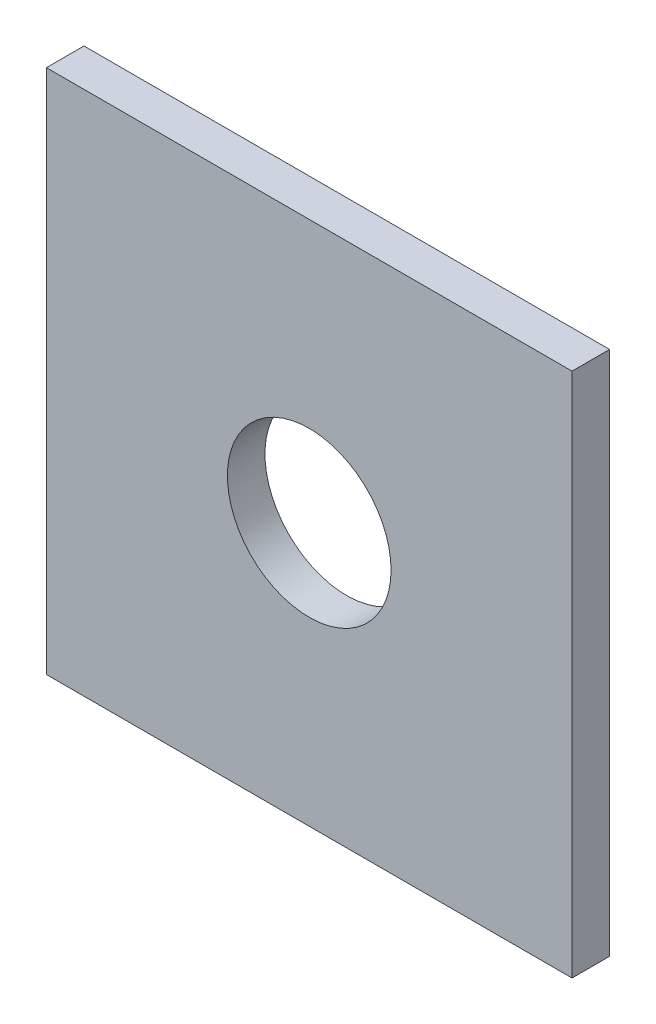
SolidWorks part; units mm, degrees
ref_plane "正面" through (0, 0, 0) normal (0, 0, 1) x (1, 0, 0)
ref_plane "平面" through (0, 0, 0) normal (0, 1, 0) x (1, 0, 0)
ref_plane "右側面" through (0, 0, 0) normal (1, 0, 0) x (0, 0, -1)
sketch "ｽｹｯﾁ2" plane through (0, 0, 0) normal (0, 0, 1) x (1, 0, 0)
  line L0 (35, 70) -> (-35, 0) construction
  line L1 (-35, 0) -> (35, 0)
  line L2 (-35, 0) -> (-35, 70)
  line L3 (-35, 70) -> (35, 70)
  line L4 (35, 0) -> (35, 70)
  line L5 (35, 0) -> (-35, 70) construction
  circle A0 centre (0, 35) radius 10.9
  point P4 (0, 0)
  dimension "D3" = 21.8
  dimension "D1" = 70
  dimension "D2" = 70
extrude "ﾎﾞｽ - 押し出し1" add sketch "ｽｹｯﾁ2" along normal blind 5
